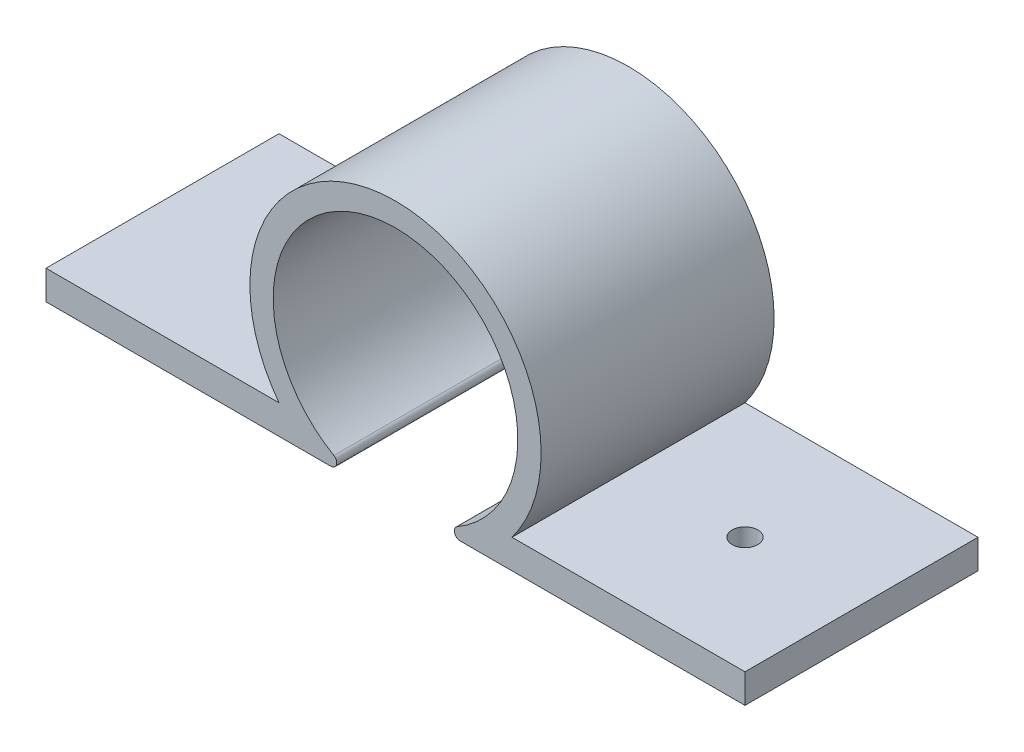
SolidWorks part; units mm, degrees
material "PVC 0.007 Plasticized"
ref_plane "Front Plane" through (0, 0, 0) normal (0, 0, 1) x (1, 0, 0)
ref_plane "Top Plane" through (0, 0, 0) normal (0, 1, 0) x (1, 0, 0)
ref_plane "Right Plane" through (0, 0, 0) normal (1, 0, 0) x (0, 0, -1)
sketch "Sketch1" plane through (0, 0, 0) normal (0, 0, 1) x (1, 0, 0)
  line L0 (10, 1.25) -> (30, 1.25)
  line L1 (-30, 1.25) -> (-10, 1.25)
  line L2 (-30, 1.25) -> (-30, -1.25)
  line L3 (-30, -1.25) -> (30, -1.25)
  line L4 (30, 1.25) -> (30, -1.25)
  line L5 (-30, 1.25) -> (30, -1.25) construction
  line L6 (-30, -1.25) -> (30, 1.25) construction
  arc A0 (10, 1.25) -> (-10, 1.25) centre (0, 8.75) ccw
  point P0 (0, 0)
  point P9 (0, -1.25)
  dimension "D3" = 25
  dimension "D1" = 60
  dimension "D2" = 2.5
  dimension "D4" = 10
sketch "Sketch2" plane through (0, 0, 0) normal (0, 0, 1) x (1, 0, 0)
  line L1 (-30, 1.25) -> (-10, 1.25) construction
  circle A0 centre (0, 8.75) radius 12.5 construction
  point P0 (-10, 1.25)
  point P1 (10, 1.25)
extrude "Boss-Extrude1" add sketch "Sketch1" along normal blind 20
sketch "Sketch3" plane through (0, 0, 20) normal (0, 0, 1) x (1, 0, 0)
  circle A0 centre (0, 8.75) radius 10.5
  arc A1 (10, 1.25) -> (-10, 1.25) centre (0, 8.75) ccw construction
  point P0 (0, 8.75)
  dimension "D1" = 21
extrude "Cut-Extrude1" cut sketch "Sketch3" against normal through all
sketch "Sketch4" plane through (0, 1.25, 0) normal (0, 1, 0) x (1, 0, 0)
  line L0 (-10, 0) -> (-30, 0) construction
  line L1 (-30, -20) -> (-30, 0) construction
  line L2 (30, 0) -> (10, 0) construction
  circle A0 centre (-20, -10) radius 1.1
  circle A1 centre (20, -10) radius 1.1
  point P7 (-20, 0)
  point P10 (-30, -10)
  point P14 (20, 0)
  dimension "D1" = 2.2
extrude "Cut-Extrude2" cut sketch "Sketch4" against normal up to surface (2.5 mm away) up to face at (-16.6008, -1.25, 10)
fillet "Fillet1" radius 0.5 2 edges at (3.2016, -1.25, 10) (-3.2016, -1.25, 10)
